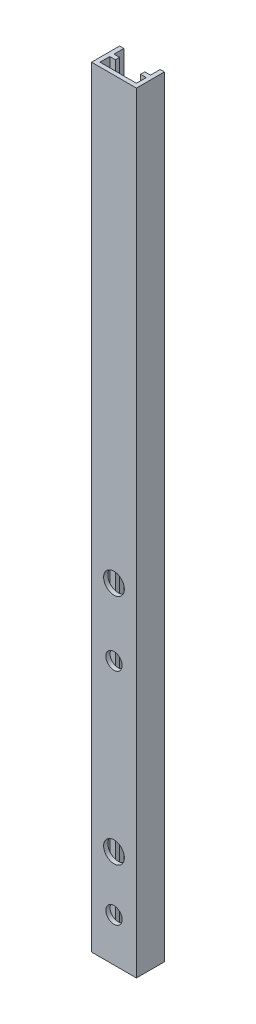
SolidWorks part; units mm, degrees
ref_plane "Front Plane" through (0, 0, 0) normal (0, 0, 1) x (1, 0, 0)
ref_plane "Top Plane" through (0, 0, 0) normal (0, 1, 0) x (1, 0, 0)
ref_plane "Right Plane" through (0, 0, 0) normal (1, 0, 0) x (0, 0, -1)
sketch "Sketch1" plane through (0, 0, 0) normal (0, 1, 0) x (1, 0, 0)
  line L0 (0, 0) -> (0, -10)
  line L1 (0, -10) -> (16, -10)
  line L2 (16, -10) -> (16, 0)
  line L3 (16, 0) -> (0, 0)
  dimension "D1" = 10
  dimension "D2" = 16
extrude "Boss-Extrude1" add sketch "Sketch1" along normal blind 275
sketch "Sketch2" plane through (0, 275, 0) normal (0, 1, 0) x (1, 0, 0)
  line L0 (1.5, 0) -> (1.5, -3.5)
  line L1 (16, 0) -> (0, 0) construction
  line L2 (1.5, -3.5) -> (3.5, -3.5)
  line L3 (3.5, -3.5) -> (3.5, -5)
  line L4 (3.5, -5) -> (1.5, -5)
  line L5 (1.5, -5) -> (1.5, -8.5)
  line L6 (1.5, -8.5) -> (14.5, -8.5)
  line L7 (14.5, -8.5) -> (14.5, -5)
  line L8 (14.5, -5) -> (12.5, -5)
  line L9 (12.5, -5) -> (12.5, -3.5)
  line L10 (12.5, -3.5) -> (14.5, -3.5)
  line L11 (14.5, -3.5) -> (14.5, 0)
  line L12 (1.5, 0) -> (14.5, 0)
  line L13 (0, 0) -> (0, -10) construction
  line L14 (16, -10) -> (16, 0) construction
  line L15 (0, -10) -> (16, -10) construction
  dimension "D1" = 1.5
  dimension "D2" = 1.5
  dimension "D3" = 1.5
  dimension "D4" = 1.5
  dimension "D5" = 1.5
  dimension "D6" = 3.5
  dimension "D7" = 2
extrude "Cut-Extrude1" cut sketch "Sketch2" against normal blind 275
sketch "Sketch3" plane through (0, 0, 10) normal (0, 0, 1) x (1, 0, 0)
  line L0 (8, 0) -> (8, 118) construction
  line L2 (0, 0) -> (16, 0) construction
  circle A0 centre (8, 15.5) radius 2.9
  circle A1 centre (8, 35) radius 3.7
  circle A2 centre (8, 94) radius 2.9
  circle A3 centre (8, 118) radius 3.7
  dimension "D1" = 7.4
  dimension "D3" = 5.8
  dimension "D5" = 118
  dimension "D6" = 94
  dimension "D7" = 35
  dimension "D8" = 15.5
extrude "Cut-Extrude2" cut sketch "Sketch3" against normal through all
